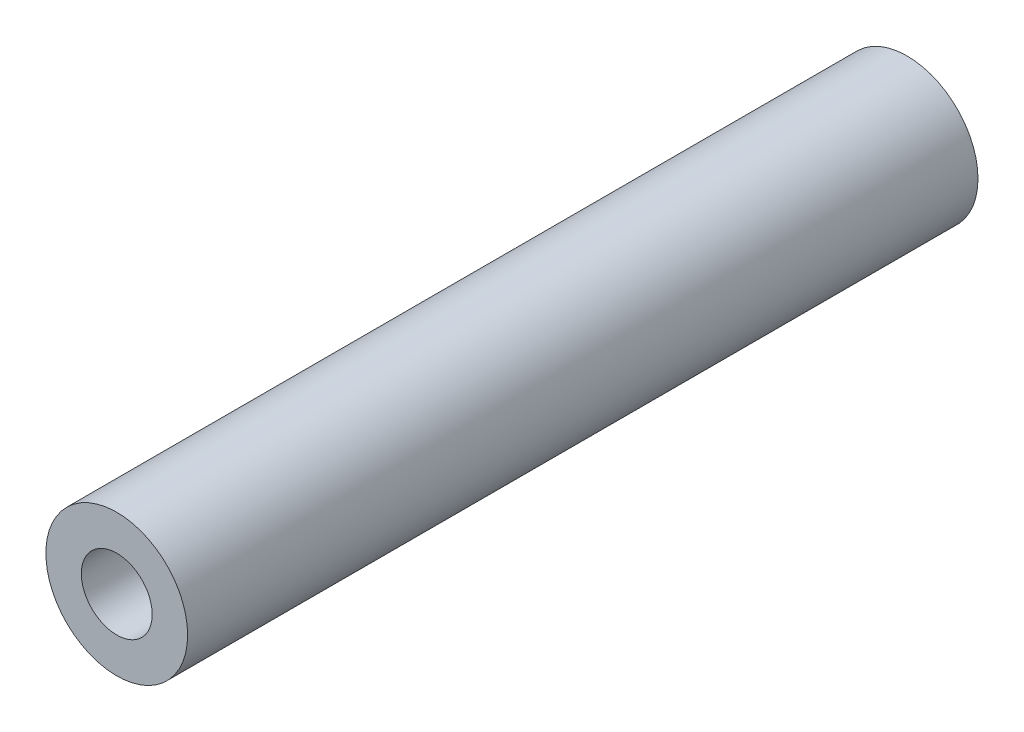
SolidWorks part; units mm, degrees
material "PET"
ref_plane "Front Plane" through (0, 0, 0) normal (0, 0, 1) x (1, 0, 0)
ref_plane "Top Plane" through (0, 0, 0) normal (0, 1, 0) x (1, 0, 0)
ref_plane "Right Plane" through (0, 0, 0) normal (1, 0, 0) x (0, 0, -1)
sketch "Sketch1" plane through (0, 0, 0) normal (0, 0, 1) x (1, 0, 0)
  circle A0 centre (0, 0) radius 4
  circle A1 centre (0, 0) radius 2
extrude "Boss-Extrude1" add sketch "Sketch1" along normal blind 44.6
